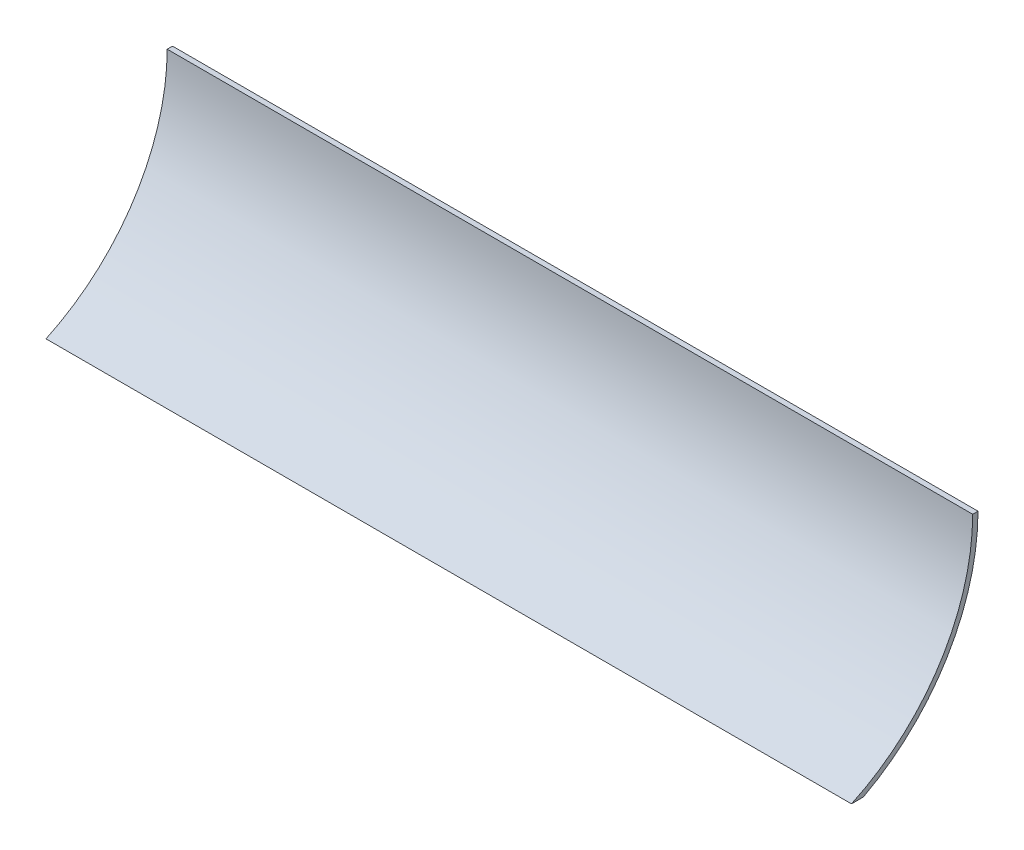
SolidWorks part; units mm, degrees
ref_plane "Front Plane" through (0, 0, 0) normal (0, 0, 1) x (1, 0, 0)
ref_plane "Top Plane" through (0, 0, 0) normal (0, 1, 0) x (1, 0, 0)
ref_plane "Right Plane" through (0, 0, 0) normal (1, 0, 0) x (0, 0, -1)
sketch "Sketch1" plane through (0, 0, 0) normal (1, 0, 0) x (0, 0, -1)
  line L0 (0, -101.6) -> (0, 0) construction
  line L1 (0, 0) -> (42.938, -92.0809) construction
  line L2 (0, 0) -> (101.6, 0) construction
  arc A0 (42.938, -92.0809) -> (101.6, 0) centre (0, 0) ccw
  arc A1 (101.6, 0) -> (0, -101.6) centre (0, 0) ccw construction
  arc A2 (0, -101.6) -> (42.938, -92.0809) centre (0, 0) ccw construction
  dimension "D1" = 203.2
  dimension "D2" = 25
extrude "Extrude-Thin1" add sketch "Sketch1" along normal mid plane 385 thin thin type mid plane wall 2.54
sketch "Sketch2" plane through (192.5, 0, 0) normal (1, 0, 0) x (0, 0, -1)
  line L0 (42.4013, -90.9299) -> (48.104, -90.9299)
  line L1 (43.4747, -93.2319) -> (42.4013, -90.9299) construction
  line L2 (43.4747, -93.2319) -> (42.4013, -90.9299)
  arc A0 (43.4747, -93.2319) -> (102.87, 0) centre (0, 0) ccw construction
  arc A1 (43.4747, -93.2319) -> (48.104, -90.9299) centre (0, 0) ccw
extrude "Cut-Extrude1" cut sketch "Sketch2" against normal through all
sketch "Sketch3" plane through (0, -90.9299, 0) normal (0, -1, 0) x (1, 0, 0)
  line L0 (192.5, -102.87) -> (-192.5, -102.87) construction
  line L1 (-192.5, -48.104) -> (-192.5, -102.87) construction
  line L2 (0, -33.2578) -> (0, 33.2578) construction
  circle A0 centre (-129, -96.52) radius 6.35
  circle A1 centre (129, -96.52) radius 6.35
  circle A2 centre (0, -96.52) radius 6.35
  point P12 (0, 0)
  point P14 (0, 0)
  dimension "D1" = 12.7
  dimension "D2" = 63.5
extrude "Boss-Extrude1" add sketch "Sketch3" against normal up to surface (90.9299 mm away)
